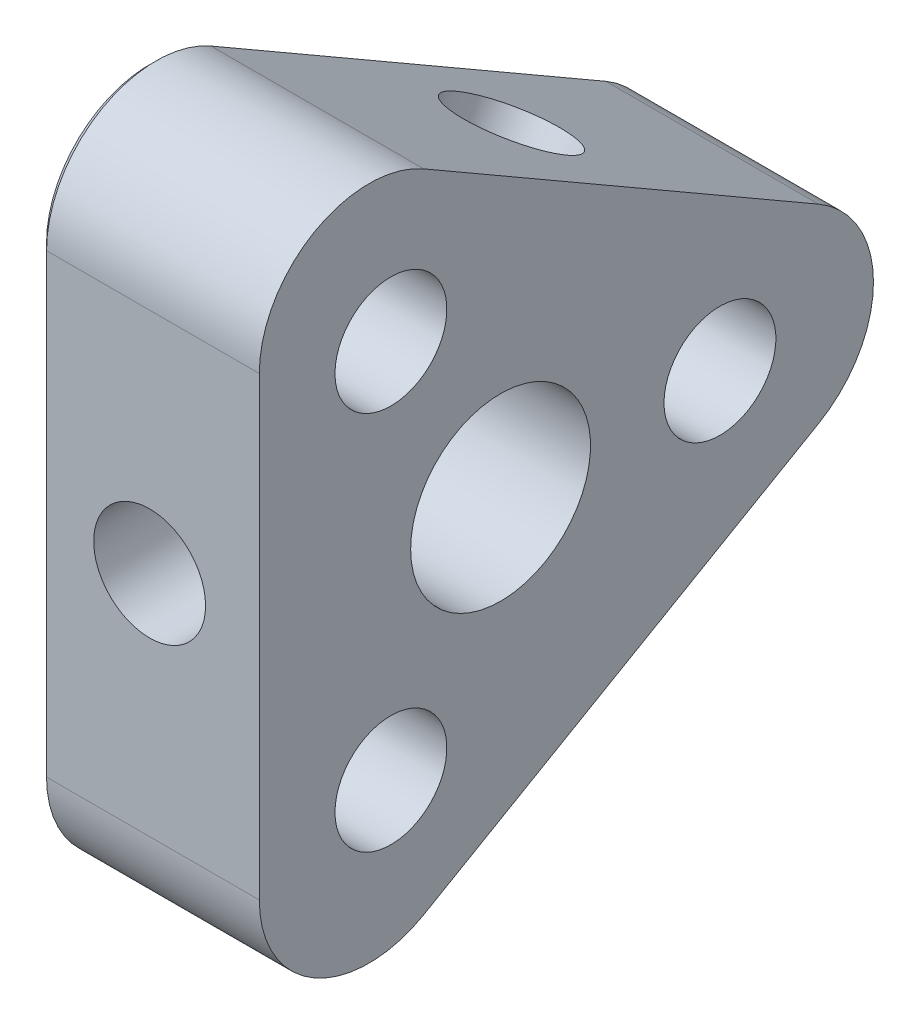
SolidWorks part; units mm, degrees
ref_plane "Front Plane" through (0, 0, 0) normal (0, 0, 1) x (1, 0, 0)
ref_plane "Top Plane" through (0, 0, 0) normal (0, 1, 0) x (1, 0, 0)
ref_plane "Right Plane" through (0, 0, 0) normal (1, 0, 0) x (0, 0, -1)
ref_plane "Plane1" through (28, 0, 0) normal (-1, 0, 0) x (0, -1, 0)
sketch "Sketch1" plane through (28, 0, 0) normal (-1, 0, 0) x (0, -1, 0)
  line L0 (-14.7224, 3.5) -> (-4.3301, -14.5)
  line L1 (4.3301, -14.5) -> (14.7224, 3.5)
  line L2 (10.3923, 11) -> (-10.3923, 11)
  arc A0 (-4.3301, -14.5) -> (4.3301, -14.5) centre (0, -12) ccw
  arc A1 (14.7224, 3.5) -> (10.3923, 11) centre (10.3923, 6) ccw
  arc A2 (-10.3923, 11) -> (-14.7224, 3.5) centre (-10.3923, 6) ccw
extrude "Boss-Extrude1" add sketch "Sketch1" against normal blind 10
hole_wizard "Ø5.1 (5.1) Diameter Hole1" positions "Sketch3" profile "Sketch2" hole size "Ø5.1" standard "ANSI Metric"
sketch "Sketch3" plane through (28, 0, 0) normal (-1, 0, 0) x (0, 0, 1)
  point P0 (-10, 0)
  point P1 (5, 8.6603)
  point P2 (5, -8.6603)
sketch "Sketch2" plane through (28, 0, -10) normal (0, 1, 0) x (0, 0, 1)
  line L0 (0, 0) -> (0, 10)
  line L1 (0, 10) -> (2.55, 10)
  line L2 (2.55, 10) -> (2.55, 0)
  line L5 (2.55, 0) -> (0, 0)
  line L11 (0, -6.35) -> (0, 107.95) construction
  dimension "Thru Hole Dia." = 5.1
  dimension "Thru Hole Depth" = 10
hole_wizard "Ø8.2 (8.2) Diameter Hole1" positions "Sketch5" profile "Sketch4" hole size "Ø8.2" standard "ANSI Metric"
sketch "Sketch5" plane through (28, 0, 0) normal (-1, 0, 0) x (0, 0, 1)
  point P0 (0, 0)
sketch "Sketch4" plane through (28, 0, 0) normal (0, 1, 0) x (0, 0, 1)
  line L0 (0, 0) -> (0, 10)
  line L1 (0, 10) -> (4.1, 10)
  line L2 (4.1, 10) -> (4.1, 0)
  line L5 (4.1, 0) -> (0, 0)
  line L11 (0, -6.35) -> (0, 107.95) construction
  dimension "Thru Hole Dia." = 8.2
  dimension "Thru Hole Depth" = 10
hole_wizard "Ø5.1 (5.1) Diameter Hole2" positions "Sketch7" profile "Sketch6" hole size "Ø5.1" standard "ANSI Metric"
sketch "Sketch7" plane through (0, 0, 11) normal (0, 0, 1) x (1, 0, 0)
  point P0 (33, 0)
sketch "Sketch6" plane through (33, 0, 11) normal (1, 0, 0) x (0, -1, 0)
  line L0 (0, 0) -> (0, 6.9)
  line L1 (0, 6.9) -> (2.55, 6.9)
  line L2 (2.55, 6.9) -> (2.55, 0)
  line L5 (2.55, 0) -> (0, 0)
  line L11 (0, -6.35) -> (0, 107.95) construction
  dimension "Thru Hole Dia." = 5.1
  dimension "Thru Hole Depth" = 6.9
chamfer "Chamfer1" distance 0.3 angle 45 10 edges at (28, 0, -7.45) (28, -14.7224, 8.5) (28, 0, 11) (28, -9.5263, -5.5) (28, 14.7224, 8.5) (28, 0, -17) (28, 9.5263, -5.5) (28, -8.6603, 7.55) (28, 8.6603, 7.55) (28, 0, 4.1)
sketch "Sketch8" plane through (0, 9.5263, -5.5) normal (0, 0.866, -0.5) x (1, 0, 0)
  line L0 (38, 10.3923) -> (28.3, 10.3923) construction
  line L1 (38, -10.3923) -> (28.3, -10.3923) construction
  line L3 (38, -10.3923) -> (38, 10.3923) construction
  line L4 (28, -10.3923) -> (28, 10.3923) construction
  circle A0 centre (33, -0.0023) radius 2.525
  point P2 (0, 0)
  point P5 (0, 0)
  point P7 (31.8461, -10.3923)
  point P11 (0, 0)
  point P14 (0, 0)
  dimension "D1" = 5.05
  dimension "D2" = 20.7846
  dimension "D3" = 10.39
  dimension "D4" = 5
  dimension "D5" = 5
extrude "Cut-Extrude1" cut sketch "Sketch8" against normal blind 8
